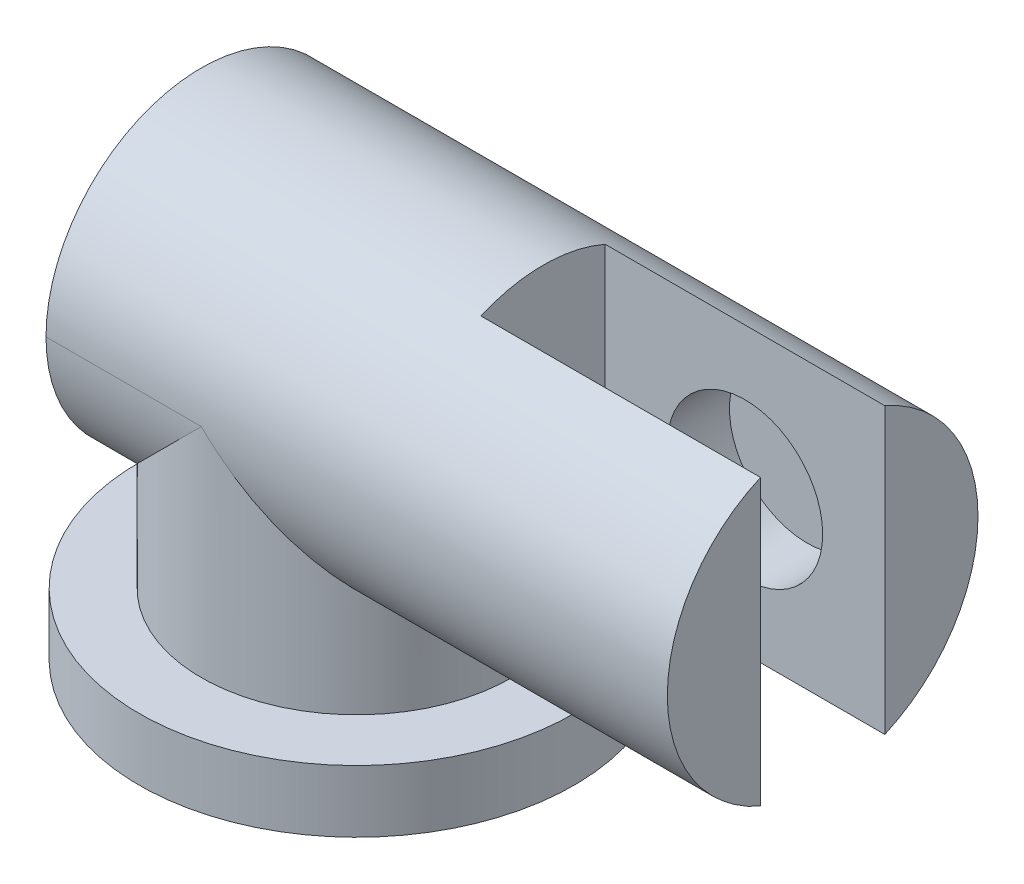
SolidWorks part; units mm, degrees
ref_plane "Front Plane" through (0, 0, 0) normal (0, 0, 1) x (1, 0, 0)
ref_plane "Top Plane" through (0, 0, 0) normal (0, 1, 0) x (1, 0, 0)
ref_plane "Right Plane" through (0, 0, 0) normal (1, 0, 0) x (0, 0, -1)
sketch "Sketch1" plane through (0, 0, 0) normal (1, 0, 0) x (0, 0, -1)
  circle A0 centre (0, 0) radius 5
  dimension "D1" = 10
extrude "Boss-Extrude1" add sketch "Sketch1" along normal blind 10
sketch "Sketch2" plane through (10, 0, 0) normal (1, 0, 0) x (0, 0, -1)
  line L1 (0, 5) -> (2, 5)
  line L2 (0, 5) -> (0, -5)
  line L3 (0, -5) -> (2, -5)
  line L4 (2, 5) -> (2, -5)
  circle A0 centre (0, 0) radius 5 construction
  dimension "D1" = 2
extrude "Cut-Extrude1" cut sketch "Sketch2" against normal blind 9
sketch "Sketch3" plane through (0, 0, -2) normal (0, 0, 1) x (1, 0, 0)
  circle A0 centre (5.5, 0) radius 2.5
  dimension "D1" = 5
extrude "Cut-Extrude2" cut sketch "Sketch3" against normal blind 2
mirror "Mirror1" about plane through (0, 0, 0) normal (0, 0, 1) of "Cut-Extrude2", "Cut-Extrude1"
sketch "Sketch4" plane through (0, 0, 0) normal (-1, 0, 0) x (0, 0, 1)
  circle A0 centre (0, 0) radius 5
extrude "Boss-Extrude2" add sketch "Sketch4" along normal blind 10
sketch "Sketch5" plane through (0, 0, 0) normal (0, 1, 0) x (1, 0, 0)
  line L0 (-10, 5) -> (-10, -5) construction
  line L1 (10, 5) -> (-10, 5) construction
  circle A0 centre (-5, 0) radius 5
  dimension "D1" = 10
  dimension "D2" = 5
  dimension "D3" = 5
extrude "Boss-Extrude3" add sketch "Sketch5" against normal blind 7
sketch "Sketch6" plane through (0, -7, 0) normal (0, -1, 0) x (1, 0, 0)
  circle A0 centre (-5, 0) radius 7
  dimension "D1" = 14
extrude "Boss-Extrude4" add sketch "Sketch6" along normal blind 2
